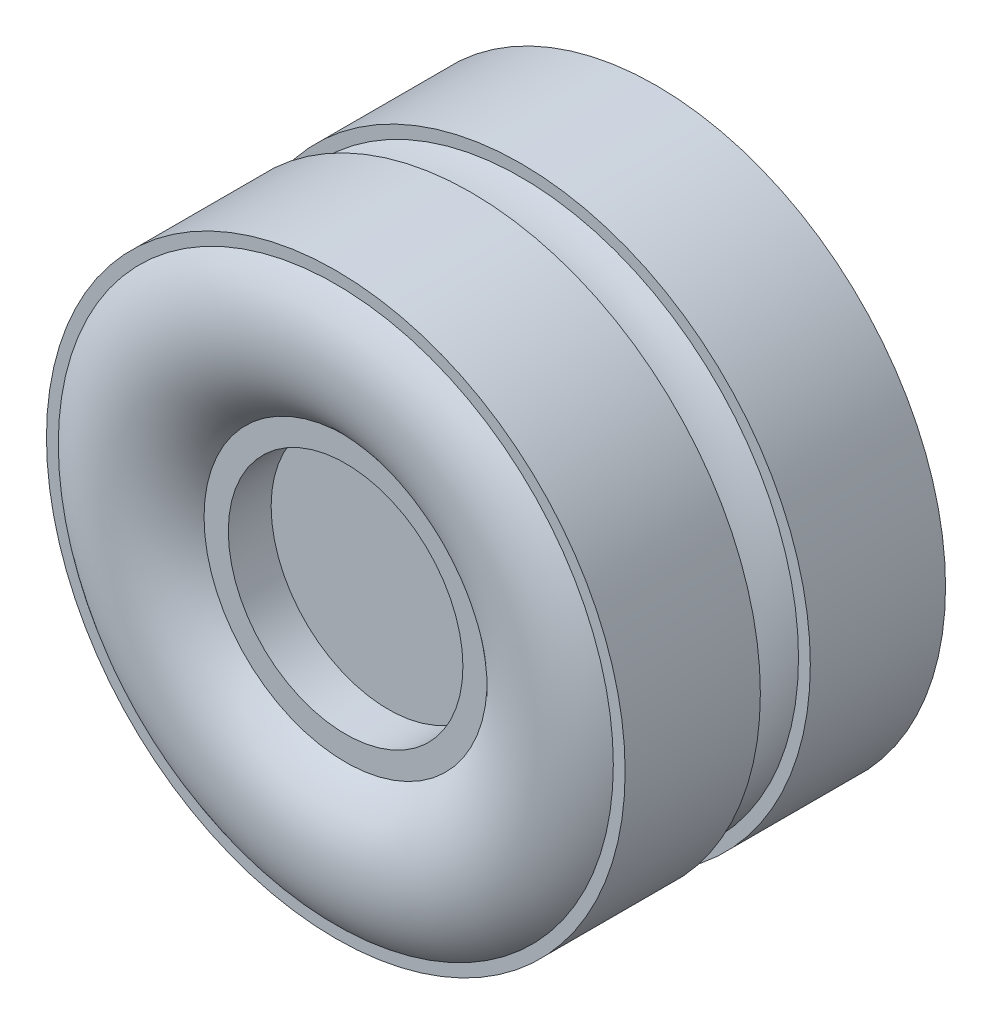
SolidWorks part; units mm, degrees
ref_plane "Front Plane" through (0, 0, 0) normal (0, 0, 1) x (1, 0, 0)
ref_plane "Top Plane" through (0, 0, 0) normal (0, 1, 0) x (1, 0, 0)
ref_plane "Right Plane" through (0, 0, 0) normal (1, 0, 0) x (0, 0, -1)
sketch "Sketch1" plane through (0, 0, 0) normal (1, 0, 0) x (0, 0, -1)
  line L0 (0, 0) -> (-78460.7107, 0) construction
  line L1 (-25.3712, 62.133) -> (-25.3712, 51.4887)
  line L2 (-25.3712, 51.4887) -> (-6.5654, 51.4887)
  line L3 (25.3712, 51.4887) -> (25.3712, 62.133)
  line L4 (-29.6735, 121.811) -> (-29.6735, 127)
  line L5 (-29.6735, 127) -> (29.6735, 127)
  line L6 (29.6735, 127) -> (29.6735, 121.811)
  line L7 (0, 0) -> (0, 78460.7107) construction
  line L8 (-6.5654, 51.4887) -> (-6.5654, 0)
  line L9 (-6.5654, 0) -> (6.9387, 0)
  line L10 (6.9387, 0) -> (6.9387, 51.4887)
  line L11 (6.9387, 51.4887) -> (25.3712, 51.4887)
  arc A0 (-25.3712, 62.133) -> (-29.6735, 121.811) centre (3.3162, 94.1952) cw
  arc A1 (25.3712, 62.133) -> (29.6735, 121.811) centre (-3.3162, 94.1952) ccw
  dimension "D2" = 79.4131
  dimension "D1" = 59.3471
  dimension "D3" = 254
revolve "Revolve1" add sketch "Sketch1" angle 360 about L0
pattern_linear "LPattern1" count 2 spacing 81.28 along (0, 0, -1) of "Revolve1"
